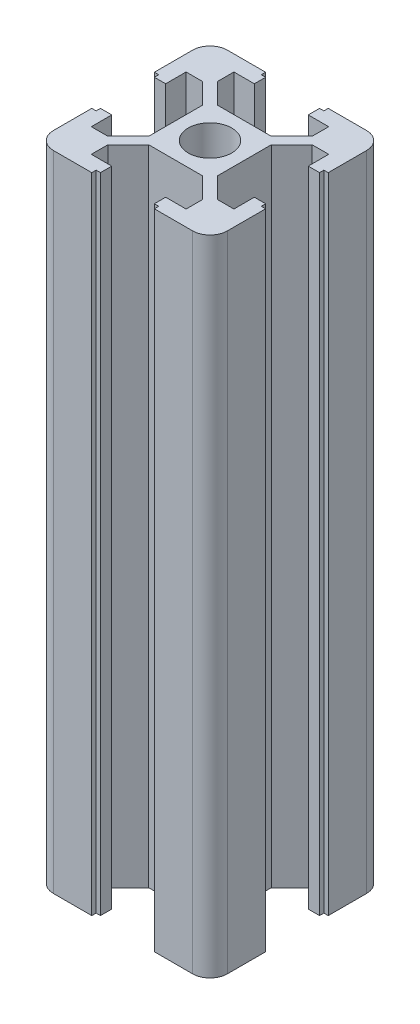
SolidWorks part; units mm, degrees
ref_plane "前视基准面" through (0, 0, 0) normal (0, 0, 1) x (1, 0, 0)
ref_plane "上视基准面" through (0, 0, 0) normal (0, 1, 0) x (1, 0, 0)
ref_plane "右视基准面" through (0, 0, 0) normal (1, 0, 0) x (0, 0, -1)
sketch "草图1" plane through (0, 0, 0) normal (0, 1, 0) x (1, 0, 0)
  line L0 (-6.2985, -5.45) -> (-3.9485, -3.1)
  line L1 (-5.45, -6.2985) -> (-3.1, -3.9485)
  line L2 (-6.2985, -5.45) -> (-8.2, -5.45)
  line L3 (-8.2, -5.45) -> (-8.2, -3.1)
  line L4 (-8.2, -3.1) -> (-10, -3.1)
  line L5 (-10, -3.1) -> (-10, -8)
  line L6 (-8, -10) -> (-3.1, -10)
  line L7 (-5.45, -6.2985) -> (-5.45, -8.2)
  line L8 (-5.45, -8.2) -> (-3.1, -8.2)
  line L9 (-3.1, -8.2) -> (-3.1, -10)
  line L10 (-3.9485, 0) -> (-3.9485, -3.1)
  line L11 (-3.1, -3.9485) -> (0, -3.9485)
  line L12 (-10, -3.6) -> (-9.5, -3.6)
  line L13 (-9.5, -3.6) -> (-9.5, -3.1)
  line L14 (-3.6, -10) -> (-3.6, -9.5)
  line L15 (-3.6, -9.5) -> (-3.1, -9.5)
  line L16 (-3.9485, 0) -> (-2.5, 0) construction
  line L17 (0, -2.5) -> (0, -3.9485) construction
  line L18 (-5.45, 6.2985) -> (-3.1, 3.9485)
  line L19 (-6.2985, 5.45) -> (-3.9485, 3.1)
  line L20 (-5.45, 6.2985) -> (-5.45, 8.2)
  line L21 (-5.45, 8.2) -> (-3.1, 8.2)
  line L22 (-3.1, 8.2) -> (-3.1, 10)
  line L23 (-3.1, 10) -> (-8, 10)
  line L24 (-10, 8) -> (-10, 3.1)
  line L25 (-6.2985, 5.45) -> (-8.2, 5.45)
  line L26 (-8.2, 5.45) -> (-8.2, 3.1)
  line L27 (-8.2, 3.1) -> (-10, 3.1)
  line L28 (-3.1, 3.9485) -> (0, 3.9485)
  line L29 (-3.9485, 3.1) -> (-3.9485, 0)
  line L30 (-3.6, 10) -> (-3.6, 9.5)
  line L31 (-3.6, 9.5) -> (-3.1, 9.5)
  line L32 (-10, 3.6) -> (-9.5, 3.6)
  line L33 (-9.5, 3.6) -> (-9.5, 3.1)
  line L34 (0, 3.9485) -> (0, 2.5) construction
  line L35 (-2.5, 0) -> (-3.9485, 0) construction
  line L36 (6.2985, 5.45) -> (3.9485, 3.1)
  line L37 (5.45, 6.2985) -> (3.1, 3.9485)
  line L38 (6.2985, 5.45) -> (8.2, 5.45)
  line L39 (8.2, 5.45) -> (8.2, 3.1)
  line L40 (8.2, 3.1) -> (10, 3.1)
  line L41 (10, 3.1) -> (10, 8)
  line L42 (8, 10) -> (3.1, 10)
  line L43 (5.45, 6.2985) -> (5.45, 8.2)
  line L44 (5.45, 8.2) -> (3.1, 8.2)
  line L45 (3.1, 8.2) -> (3.1, 10)
  line L46 (3.9485, 0) -> (3.9485, 3.1)
  line L47 (3.1, 3.9485) -> (0, 3.9485)
  line L48 (10, 3.6) -> (9.5, 3.6)
  line L49 (9.5, 3.6) -> (9.5, 3.1)
  line L50 (3.6, 10) -> (3.6, 9.5)
  line L51 (3.6, 9.5) -> (3.1, 9.5)
  line L52 (3.9485, 0) -> (2.5, 0) construction
  line L53 (0, 2.5) -> (0, 3.9485) construction
  line L54 (5.45, -6.2985) -> (3.1, -3.9485)
  line L55 (6.2985, -5.45) -> (3.9485, -3.1)
  line L56 (5.45, -6.2985) -> (5.45, -8.2)
  line L57 (5.45, -8.2) -> (3.1, -8.2)
  line L58 (3.1, -8.2) -> (3.1, -10)
  line L59 (3.1, -10) -> (8, -10)
  line L60 (10, -8) -> (10, -3.1)
  line L61 (6.2985, -5.45) -> (8.2, -5.45)
  line L62 (8.2, -5.45) -> (8.2, -3.1)
  line L63 (8.2, -3.1) -> (10, -3.1)
  line L64 (0, -3.9485) -> (3.1, -3.9485)
  line L65 (3.9485, -3.1) -> (3.9485, 0)
  line L66 (3.6, -10) -> (3.6, -9.5)
  line L67 (3.6, -9.5) -> (3.1, -9.5)
  line L68 (10, -3.6) -> (9.5, -3.6)
  line L69 (9.5, -3.6) -> (9.5, -3.1)
  line L70 (0, -3.9485) -> (0, -2.5) construction
  line L71 (2.5, 0) -> (3.9485, 0) construction
  line L72 (0, 3.9485) -> (-3.1, 3.9485) [skipped]
  circle A0 centre (0, 0) radius 2.5
  arc A1 (-10, -8) -> (-8, -10) centre (-8, -8) ccw
  arc A3 (-8, 10) -> (-10, 8) centre (-8, 8) ccw
  arc A5 (10, 8) -> (8, 10) centre (8, 8) ccw
  arc A7 (8, -10) -> (10, -8) centre (8, -8) ccw
  point P25 (-10, -10)
  point P98 (0, 0)
  dimension "D9" = 2
  dimension "D15" = 5
  dimension "D2" = 1.2
  dimension "D4" = 5.45
  dimension "D5" = 1.8
  dimension "D6" = 3.1
  dimension "D7" = 135
  dimension "D10" = 0.5
  dimension "D11" = 0.5
  dimension "D12" = 0.5
  dimension "D13" = 0.5
  dimension "D14" = 4
extrude "凸台-拉伸1" add sketch "草图1" along normal blind 74 contours L59 A7 L60 L68 L69 L63 L62 L61 L55 L65 L46 L36 L38 L39 L40 L49 L48 L41 A5 L42 L50 L51 L45 L44 L43 L37 L47 L28 L18 L20 L21 L22 L31 L30 L23 A3 L24 L32 L33 L27 L26 L25 L19 L29 L10 L0 L2 L3 L4 L13 L12
